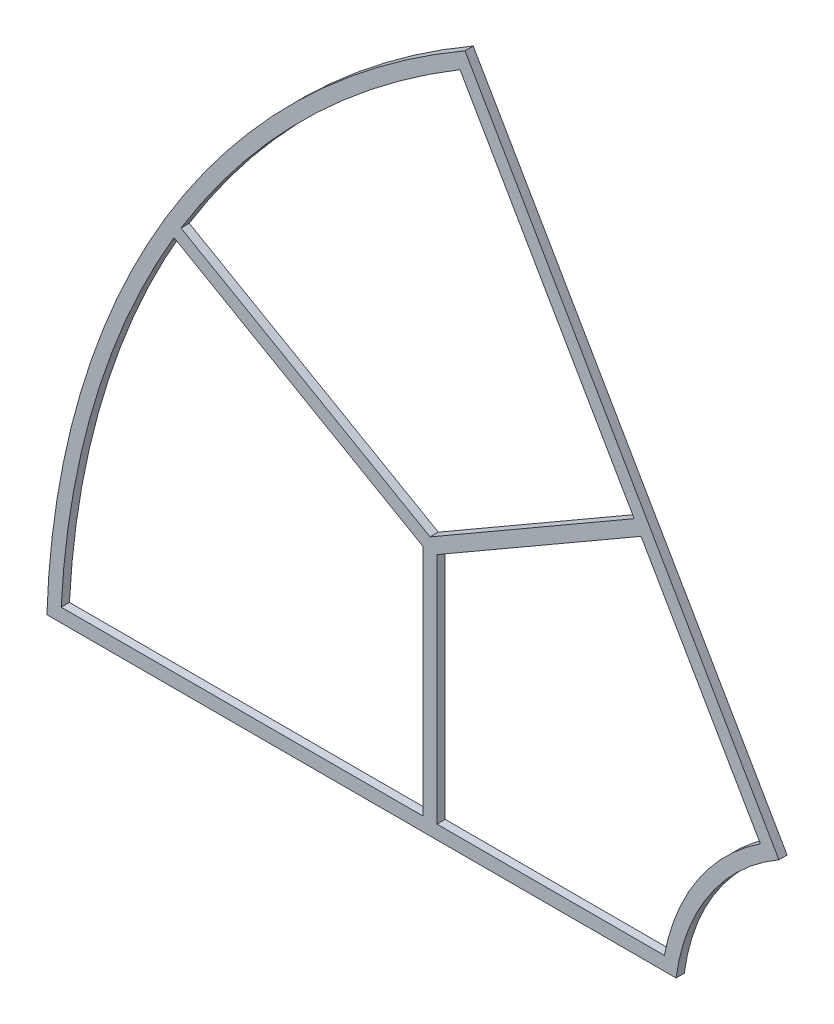
SolidWorks part; units mm, degrees
ref_plane "Front Plane" through (0, 0, 0) normal (0, 0, 1) x (1, 0, 0)
ref_plane "Top Plane" through (0, 0, 0) normal (0, 1, 0) x (1, 0, 0)
ref_plane "Right Plane" through (0, 0, 0) normal (1, 0, 0) x (0, 0, -1)
sketch "Sketch1" plane through (0, 0, 0) normal (0, 0, 1) x (1, 0, 0)
  line L1 (-151.082, 20) -> (-609.6, 20)
  line L2 (-76.2, 131.9823) -> (-304.8, 527.9291)
  line L3 (-520.2684, 317.6995) -> (-520.3687, 317.7571)
  line L4 (-151.082, 20) -> (-609.2718, 20)
  line L5 (-335.2, 199.9666) -> (-516.7369, 304.1433)
  line L6 (-330.2076, 208.6312) -> (-511.5918, 312.7203)
  line L7 (-89.7062, 135.3756) -> (-176.5521, 285.7972)
  line L8 (-159.605, 30) -> (-325.2, 30)
  line L9 (-123.5362, 90.0309) -> (-131.8552, 94.8048)
  line L10 (-325.2, 30) -> (-325.2, 199.9754)
  line L11 (-325.2, 199.9754) -> (-176.5521, 285.7972)
  line L12 (-128.5135, 81.3575) -> (-137.4539, 86.4881)
  line L13 (-335.2, 30) -> (-335.2, 199.9666)
  line L14 (-330.2076, 208.6312) -> (-181.5521, 294.4575)
  line L15 (-181.5521, 294.4575) -> (-308.4186, 514.1966)
  line L16 (-335.2, 30) -> (-598.849, 30)
  line L17 (-89.7062, 135.3756) -> (-308.4186, 514.1966) construction
  line L19 (-159.605, 30) -> (-598.849, 30) construction
  arc A0 (-304.8, 527.9291) -> (-609.2718, 20) centre (0, 0) ccw
  arc A1 (-76.2, 131.9823) -> (-151.082, 20) centre (0, 0) ccw
  arc A2 (-89.7062, 135.3756) -> (-159.605, 30) centre (0, 0) ccw
  arc A3 (-308.4186, 514.1966) -> (-511.5918, 312.7203) centre (0, 0) ccw
  arc A4 (-516.7369, 304.1433) -> (-598.849, 30) centre (0, 0) ccw
  arc A6 (-308.4186, 514.1966) -> (-598.849, 30) centre (0, 0) ccw construction
  point P3 (0, 20)
  point P9 (0, 0)
  dimension "D1" = 10
extrude "Boss-Extrude1" add sketch "Sketch1" along normal blind 6
